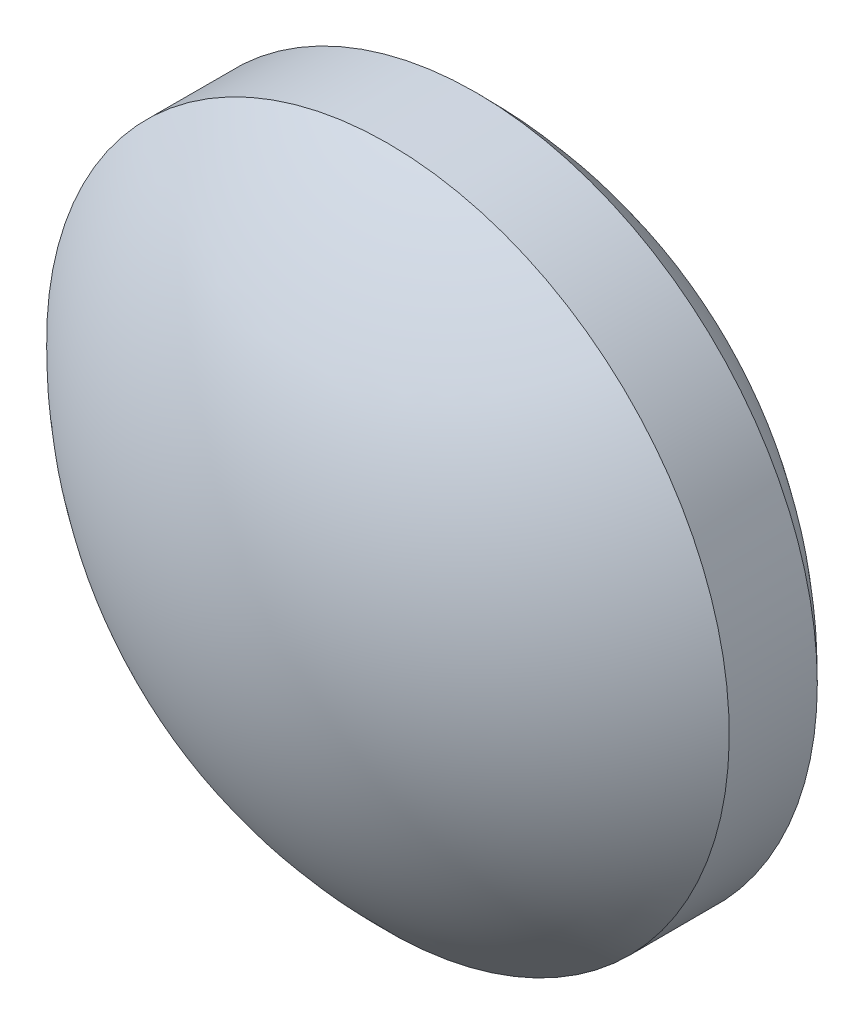
SolidWorks part; units mm, degrees
ref_plane "Front Plane" through (0, 0, 0) normal (0, 0, 1) x (1, 0, 0)
ref_plane "Top Plane" through (0, 0, 0) normal (0, 1, 0) x (1, 0, 0)
ref_plane "Right Plane" through (0, 0, 0) normal (1, 0, 0) x (0, 0, -1)
sketch "Sketch3" plane through (0, 0, 0) normal (1, 0, 0) x (0, 0, -1)
  line L0 (-2.1391, 0) -> (2.1391, 0)
  line L1 (0, 0) -> (0, 3.875)
  line L2 (-0.5, 3.875) -> (0.5, 3.875)
  line L3 (0, 0) -> (-3.2609, 0)
  arc A0 (2.1391, 0) -> (0.5, 3.875) centre (-3.2609, 0) ccw
  arc A1 (-2.1391, 0) -> (-0.5, 3.875) centre (3.2609, 0) cw
  dimension "D1" = 2.1391
  dimension "D2" = 3.875
  dimension "D3" = 0.5
  dimension "D4" = 3.2609
revolve "Revolve1" add sketch "Sketch3" angle 360 about L3
equation "\"T_edge\"= \"gloabl_scale\" * 1mm"
equation "\"R\"= \"gloabl_scale\" * 5.4mm"
equation "\"dT_c\"= \"R\" * ( 1 - sqr ( 1 - \"h\" ^ 2 / \"R\" ^ 2 ) )"
equation "\"h\"= \"gloabl_scale\" * 7.75 / 2mm"
equation "\"gloabl_scale\"= 1"
equation "\"x_sphere_origin\"= \"R\" - \"dT_c\" - \"T_edge\" / 2"
equation "\"T_c\"= \"T_edge\" + 2 * \"dT_c\""
equation "\"D1@Sketch3\"=\"T_c\" / 2"
equation "\"D2@Sketch3\"=\"h\""
equation "\"D3@Sketch3\"=\"T_edge\" / 2"
equation "\"D4@Sketch3\"=\"x_sphere_origin\""
